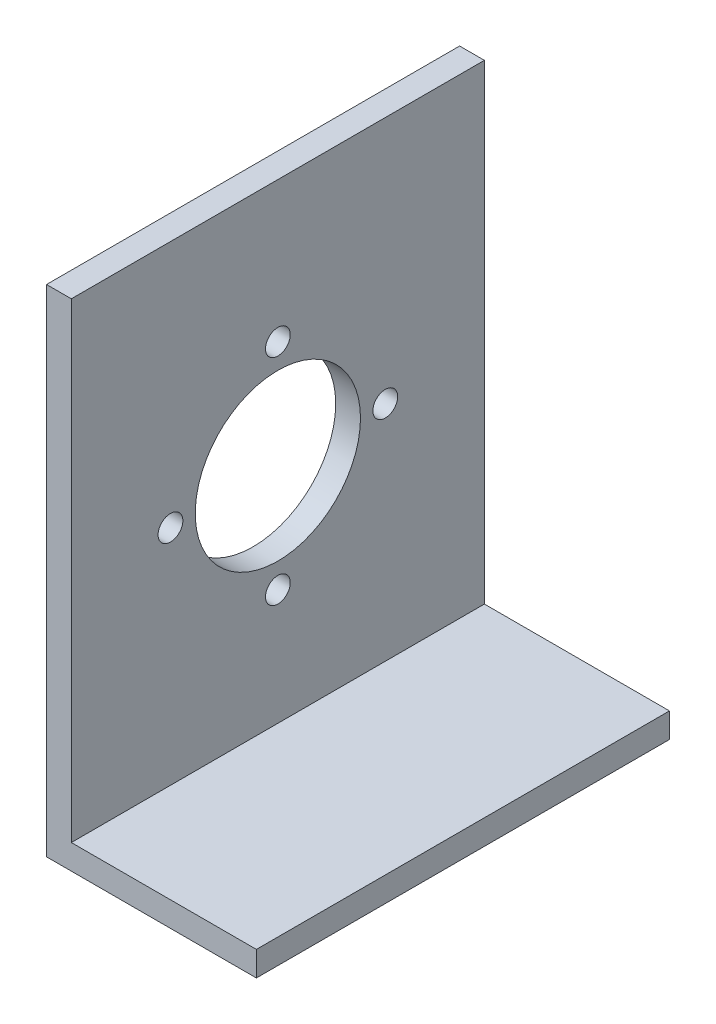
SolidWorks part; units mm, degrees
material "1060 Alloy"
ref_plane "Front Plane" through (0, 0, 0) normal (0, 0, 1) x (1, 0, 0)
ref_plane "Top Plane" through (0, 0, 0) normal (0, 1, 0) x (1, 0, 0)
ref_plane "Right Plane" through (0, 0, 0) normal (1, 0, 0) x (0, 0, -1)
sketch "Sketch1" plane through (0, 0, 0) normal (0, 0, 1) x (1, 0, 0)
  line L0 (0, 0) -> (0, -60)
  line L1 (0, -60) -> (25.4, -60)
  line L2 (3, 0) -> (3, -57)
  line L3 (3, -57) -> (25.4, -57)
  line L4 (3, 0) -> (0, 0)
  line L5 (25.4, -57) -> (25.4, -60)
  dimension "D1" = 3
extrude "Boss-Extrude1" add sketch "Sketch1" along normal blind 50
sketch "Sketch2" plane through (3, 0, 0) normal (1, 0, 0) x (0, 0, -1)
  circle A2 centre (-25, -30) radius 10
  circle A3 centre (-25, -17) radius 1.5
  circle A4 centre (-12, -30) radius 1.5
  circle A5 centre (-25, -43) radius 1.5
  circle A6 centre (-38, -30) radius 1.5
  point P18 (-25, -30)
  dimension "D1" = 4
extrude "Cut-Extrude1" cut sketch "Sketch2" against normal blind 50
